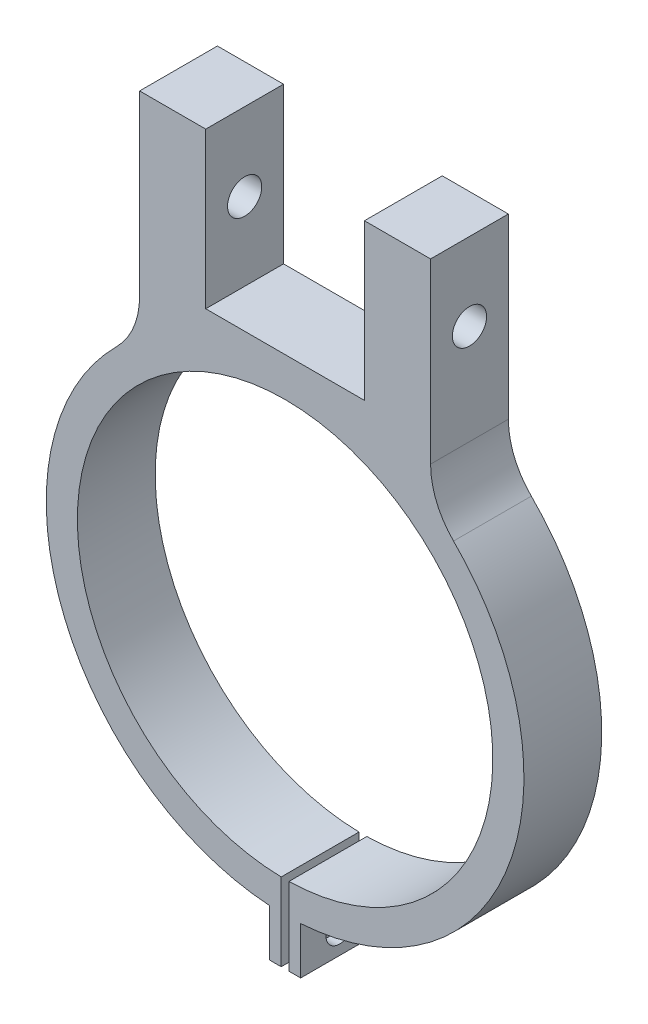
SolidWorks part; units mm, degrees
ref_plane "Ebene vorne" through (0, 0, 0) normal (0, 0, 1) x (1, 0, 0)
ref_plane "Ebene oben" through (0, 0, 0) normal (0, 1, 0) x (1, 0, 0)
ref_plane "Ebene rechts" through (0, 0, 0) normal (1, 0, 0) x (0, 0, -1)
sketch "Skizze1" plane through (0, 0, 0) normal (0, 0, 1) x (1, 0, 0)
  line L0 (0, 0) -> (0, 53.7291) construction
  line L14 (0, 0) -> (0, -44.1347) construction
  line L15 (0.5, -26.6953) -> (0.5, -30.6959)
  line L16 (-0.5, -26.6953) -> (-0.5, -30.6959)
  line L17 (0.5, -30.6959) -> (0.5, -36.6959)
  line L18 (0.5, -36.6959) -> (2, -36.6959)
  line L19 (2, -36.6959) -> (2, -30.6348)
  line L20 (-2, -36.6959) -> (-2, -30.6348)
  line L21 (-0.5, -36.6959) -> (-2, -36.6959)
  line L22 (-0.5, -30.6959) -> (-0.5, -36.6959)
  line L23 (-10.2, 31.7) -> (-10.2, 51.7)
  line L24 (-10.2, 51.7) -> (-18.7, 51.7)
  line L25 (-18.7, 51.7) -> (-18.7, 24.3475)
  line L26 (-10.2, 31.7) -> (10.2, 31.7)
  line L27 (0, 26.7) -> (12.0002, 26.7) construction
  line L28 (18.7, 51.7) -> (18.7, 24.3475)
  line L29 (10.2, 51.7) -> (18.7, 51.7)
  line L30 (10.2, 31.7) -> (10.2, 51.7)
  arc A0 (0.5, -26.6953) -> (-0.5, -26.6953) centre (0, 0) ccw
  arc A1 (-18.7, 24.3475) -> (-2, -30.6348) centre (0, 0) ccw
  arc A2 (2, -30.6348) -> (18.7, 24.3475) centre (0, 0) ccw
  point P10 (0, 33.5025)
  point P11 (0, 31.6594)
  point P17 (0, 31.7)
  point P18 (0, 39.6025)
  dimension "D1" = 53.4
  dimension "D2" = 4
  dimension "D3" = 20.4
  dimension "D4" = 20
  dimension "D5" = 5
  dimension "D6" = 8.5
  dimension "D10" = 1
  dimension "D11" = 1.5
  dimension "D12" = 6
extrude "Aufsatz-Linear austragen1" add sketch "Skizze1" along normal blind 10
sketch "Skizze2" plane through (-2, 0, 0) normal (-1, 0, 0) x (0, 0, 1)
  line L0 (0, -33.6654) -> (10, -33.6654) construction
  line L1 (0, -30.6348) -> (0, -36.6959) construction
  line L2 (10, -30.6348) -> (10, -36.6959) construction
  circle A0 centre (5, -33.6654) radius 1.75
  dimension "D1" = 3.5
extrude "Schnitt-Linear austragen1" cut sketch "Skizze2" against normal through all
sketch "Skizze3" plane through (0, 0, 10) normal (0, 0, 1) x (1, 0, 0)
  line L0 (-10.8174, 36.4205) -> (0, 26.8755)
  line L1 (0, 26.8755) -> (11.8484, 37.1414)
  line L2 (11.8484, 37.1414) -> (47.3746, 17.8863)
  line L3 (47.3746, 17.8863) -> (51.4546, -59.0738)
  line L4 (51.4546, -59.0738) -> (-81.1349, -43.2704)
  line L5 (-81.1349, -43.2704) -> (-40.9452, 68.8874)
  line L6 (-40.9452, 68.8874) -> (-10.8174, 36.4205)
extrude "Schnitt-Linear austragen2" [suppressed] cut sketch "Skizze3" against normal through all
sketch "Skizze4" plane through (-18.7, 0, 0) normal (-1, 0, 0) x (0, 0, 1)
  line L0 (5, 51.7) -> (5, 31.7) construction
  line L1 (10, 51.7) -> (0, 51.7) construction
  line L3 (10, 31.7) -> (0, 31.7) construction
  circle A0 centre (5, 41.7) radius 2.2
  dimension "D1" = 4.4
extrude "Schnitt-Linear austragen3" cut sketch "Skizze4" against normal through all
fillet "Verrundung1" radius 10 2 edges at (18.7, 24.3475, 5) (-18.7, 24.3475, 5)
